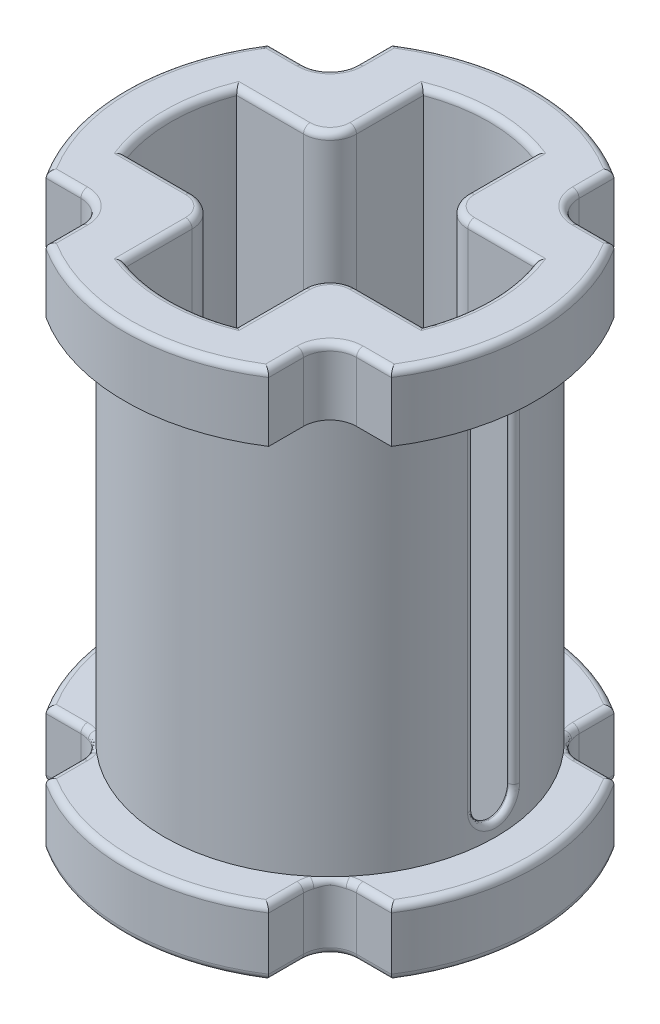
SolidWorks part; units mm, degrees
ref_plane "Front Plane" through (0, 0, 0) normal (0, 0, 1) x (1, 0, 0)
ref_plane "Top Plane" through (0, 0, 0) normal (0, 1, 0) x (1, 0, 0)
ref_plane "Right Plane" through (0, 0, 0) normal (1, 0, 0) x (0, 0, -1)
sketch "Sketch8" plane through (0, 0, 0) normal (0, 1, 0) x (1, 0, 0)
  circle A0 centre (0, 0) radius 3.1
  dimension "D1" = 6.2
extrude "Boss-Extrude4" add sketch "Sketch8" along normal blind 8
sketch "Sketch9" plane through (0, 0, 0) normal (0, 1, 0) x (1, 0, 0)
  line L0 (1.24, 0.84) -> (2.2482, 0.84)
  line L2 (-0.84, 2.2482) -> (-0.84, 1.24)
  line L4 (0.84, 2.2482) -> (0.84, 1.24)
  line L5 (-0.84, 2.2482) -> (0.84, -2.2482) construction
  line L6 (-0.84, -2.2482) -> (0.84, 2.2482) construction
  line L7 (-2.2482, 0.84) -> (-1.24, 0.84)
  line L9 (-2.2482, -0.84) -> (-1.24, -0.84)
  line L11 (-2.2482, 0.84) -> (2.2482, -0.84) construction
  line L12 (-2.2482, -0.84) -> (2.2482, 0.84) construction
  line L13 (1.24, -0.84) -> (2.2482, -0.84)
  line L14 (-0.84, -1.24) -> (-0.84, -2.2482)
  line L15 (0.84, -1.24) -> (0.84, -2.2482)
  circle A0 centre (0, 0) radius 2.4
  arc A1 (1.24, -0.84) -> (0.84, -1.24) centre (1.24, -1.24) ccw
  arc A2 (-1.24, -0.84) -> (-0.84, -1.24) centre (-1.24, -1.24) cw
  arc A3 (1.24, 0.84) -> (0.84, 1.24) centre (1.24, 1.24) cw
  arc A4 (-1.24, 0.84) -> (-0.84, 1.24) centre (-1.24, 1.24) ccw
  point P17 (0.84, -0.84)
  point P20 (-0.84, -0.84)
  dimension "D1" = 4.8
  dimension "D4" = 0.4
  dimension "D2" = 1.68
  dimension "D3" = 1.68
extrude "Cut-Extrude1" cut sketch "Sketch9" along normal blind 10 contours A4 L7 A0 L9 A2 L14 L15 A1 L13 L0 A3 L4 L2
sketch "Sketch10" plane through (0, 0, 0) normal (0, -1, 0) x (1, 0, 0)
  line L0 (-2.08, -1.68) -> (-2.6053, -1.68)
  line L2 (1.68, -2.6053) -> (1.68, -2.08)
  line L4 (-1.68, -2.6053) -> (-1.68, -2.08)
  line L5 (1.68, -2.6053) -> (1.0833, -1.68) construction
  line L6 (1.68, 2.6053) -> (-1.68, -2.6053) construction
  line L7 (2.6053, -1.68) -> (2.08, -1.68)
  line L9 (2.6053, 1.68) -> (2.08, 1.68)
  line L11 (2.6053, -1.68) -> (-2.6053, 1.68) construction
  line L12 (2.6053, 1.68) -> (-2.6053, -1.68) construction
  line L13 (0, 0) -> (-1.68, 2.6053) construction
  line L14 (1.68, 2.08) -> (1.68, 2.6053)
  line L15 (-2.08, 1.68) -> (-2.6053, 1.68)
  line L16 (-1.68, 2.08) -> (-1.68, 2.6053)
  circle A0 centre (0, 0) radius 3.1 construction
  arc A1 (1.68, 2.08) -> (2.08, 1.68) centre (2.08, 2.08) ccw
  arc A2 (-2.08, 1.68) -> (-1.68, 2.08) centre (-2.08, 2.08) ccw
  arc A3 (-2.08, -1.68) -> (-1.68, -2.08) centre (-2.08, -2.08) cw
  arc A4 (2.08, -1.68) -> (1.68, -2.08) centre (2.08, -2.08) ccw
  circle A5 centre (0, 0) radius 3.1
  point P0 (0, 0)
  point P8 (0, 0)
  point P23 (-1.68, 1.68)
  circle M19 centre (0, 0) radius 3.1
  dimension "D3" = 0.4
  dimension "D1" = 3.36
  dimension "D2" = 3.36
extrude "Cut-Extrude2" cut sketch "Sketch10" against normal blind 9 contours L7 A4 L2 M19 | A3 L0 L4 M19 | L15 A2 L16 M19 | L14 A1 L9 M19
ref_plane "Plane1" through (0, 4, 0) normal (0, 1, 0) x (1, 0, 0)
sketch "Sketch13" plane through (0, 4, 0) normal (0, 1, 0) x (1, 0, 0)
  circle A0 centre (0, 0) radius 2.5
  circle A1 centre (0, 0) radius 3.1
  dimension "D1" = 5
  dimension "D2" = 6.2
extrude "Cut-Extrude4" cut sketch "Sketch13" against normal mid plane 6
fillet "Fillet1" radius 0.1 32 edges at (-2.3427, 0, -1.68) (-1.7972, 0, -1.7972) (-1.68, 0, 2.3427) (-1.7972, 0, 1.7972) (1.68, 0, 2.3427) (1.7972, 0, 1.7972) (-3.1, 0, 0) (-1.68, 0, -2.3427) (-2.3427, 0, 1.68) (2.3427, 0, 1.68) (0, 0, 3.1) (3.1, 0, 0) (0, 0, -3.1) (2.3427, 0, -1.68) (1.7972, 0, -1.7972) (1.68, 0, -2.3427) (0, 0, -2.4) (0.84, 0, -1.7441) (0.9572, 0, -0.9572) (1.7441, 0, -0.84) (2.4, 0, 0) (1.7441, 0, 0.84) (0.9572, 0, 0.9572) (0.84, 0, 1.7441) (0, 0, 2.4) (-0.84, 0, 1.7441) (-0.9572, 0, 0.9572) (-1.7441, 0, 0.84) (-2.4, 0, 0) (-1.7441, 0, -0.84) (-0.9572, 0, -0.9572) (-0.84, 0, -1.7441)
fillet "Fillet2" radius 0.1 32 edges at (-1.68, 8, 2.3427) (-1.7972, 8, 1.7972) (-2.3427, 8, 1.68) (-3.1, 8, 0) (-2.3427, 8, -1.68) (-1.7972, 8, -1.7972) (-1.68, 8, -2.3427) (0, 8, -3.1) (1.68, 8, -2.3427) (1.7972, 8, -1.7972) (2.3427, 8, -1.68) (3.1, 8, 0) (2.3427, 8, 1.68) (1.7972, 8, 1.7972) (1.68, 8, 2.3427) (0, 8, 3.1) (-1.7441, 8, -0.84) (-2.4, 8, 0) (-1.7441, 8, 0.84) (-0.9572, 8, 0.9572) (-0.84, 8, 1.7441) (0, 8, 2.4) (0.84, 8, 1.7441) (0.9572, 8, 0.9572) (1.7441, 8, 0.84) (2.4, 8, 0) (1.7441, 8, -0.84) (0.9572, 8, -0.9572) (0.84, 8, -1.7441) (0, 8, -2.4) (-0.84, 8, -1.7441) (-0.9572, 8, -0.9572)
sketch "Sketch15" plane through (0, 0, 0) normal (1, 0, 0) x (0, 0, -1)
  line L0 (0, 6.5) -> (0, 1.5) construction
  line L5 (3.3, 4) -> (-3.3, 4) construction
  line L6 (0.3, 6.5) -> (0.3, 1.5)
  line L7 (-0.3, 6.5) -> (-0.3, 1.5)
  arc A2 (0.3, 6.5) -> (-0.3, 6.5) centre (0, 6.5) ccw
  arc A3 (-0.3, 1.5) -> (0.3, 1.5) centre (0, 1.5) ccw
  point P4 (0, 4)
  dimension "D2" = 0.3
  dimension "D1" = 5
extrude "Cut-Extrude5" cut sketch "Sketch15" along normal blind 3 and the other way blind 3
fillet "Fillet4" radius 0.1 16 edges at (1.68, 1, 2.3427) (1.7972, 1, 1.7972) (2.3427, 1, -1.68) (1.7972, 1, -1.7972) (-1.68, 1, 2.3427) (-1.7972, 1, 1.7972) (-1.68, 1, -2.3427) (-1.7972, 1, -1.7972) (2.3427, 1, 1.68) (1.68, 1, -2.3427) (3.1, 1, 0) (-2.3427, 1, 1.68) (0, 1, 3.1) (0, 1, -3.1) (-2.3427, 1, -1.68) (-3.1, 1, 0)
fillet "Fillet5" radius 0.08 8 edges at (2.4998, 6.7981, 0.0337) (-2.4998, 6.7981, -0.0337) (2.4819, 4, 0.3) (-2.4819, 4, 0.3) (2.4998, 1.2019, -0.0337) (-2.4998, 1.2019, 0.0337) (2.4819, 4, -0.3) (-2.4819, 4, -0.3)
